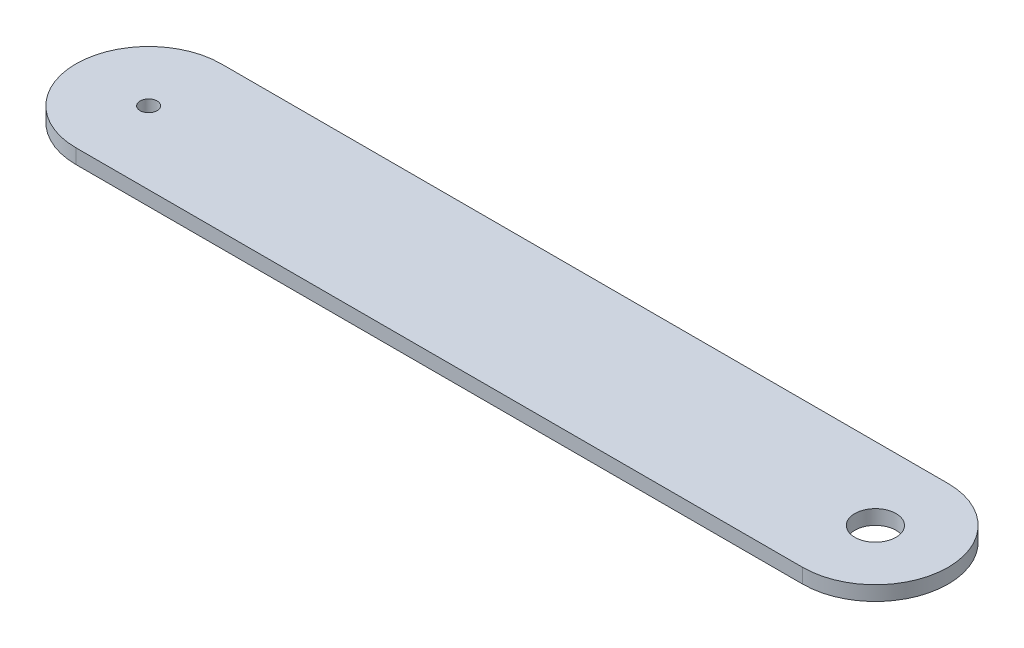
SolidWorks part; units mm, degrees
ref_plane "Plano frontal" through (0, 0, 0) normal (0, 0, 1) x (1, 0, 0)
ref_plane "Plano superior" through (0, 0, 0) normal (0, 1, 0) x (1, 0, 0)
ref_plane "Plano direito" through (0, 0, 0) normal (1, 0, 0) x (0, 0, -1)
sketch "Esboço3" plane through (0, 0, 0) normal (0, 1, 0) x (1, 0, 0)
  line L2 (-50, 15) -> (100, 15)
  line L3 (-50, -15) -> (100, -15)
  arc A0 (100, 15) -> (100, -15) centre (100, 0) cw
  arc A1 (-50, 15) -> (-50, -15) centre (-50, 0) ccw
  point P4 (0, 0)
  dimension "D2" = 30
  dimension "D4" = 15
  dimension "D1" = 150
  dimension "D5" = 50
extrude "Ressalto-extrusão2" add sketch "Esboço3" along normal blind 3
sketch "Esboço4" plane through (0, 3, 0) normal (0, 1, 0) x (1, 0, 0)
  line L0 (-65, 0) -> (115, 0) construction
  arc A0 (-50, 15) -> (-50, -15) centre (-50, 0) ccw construction
  arc A1 (100, -15) -> (100, 15) centre (100, 0) ccw construction
  circle A2 centre (-50, 0) radius 1.75
  circle A3 centre (100, 0) radius 4.25
  dimension "D1" = 3.5
  dimension "D2" = 8.5
extrude "Corte-extrusão1" cut sketch "Esboço4" against normal blind 10
